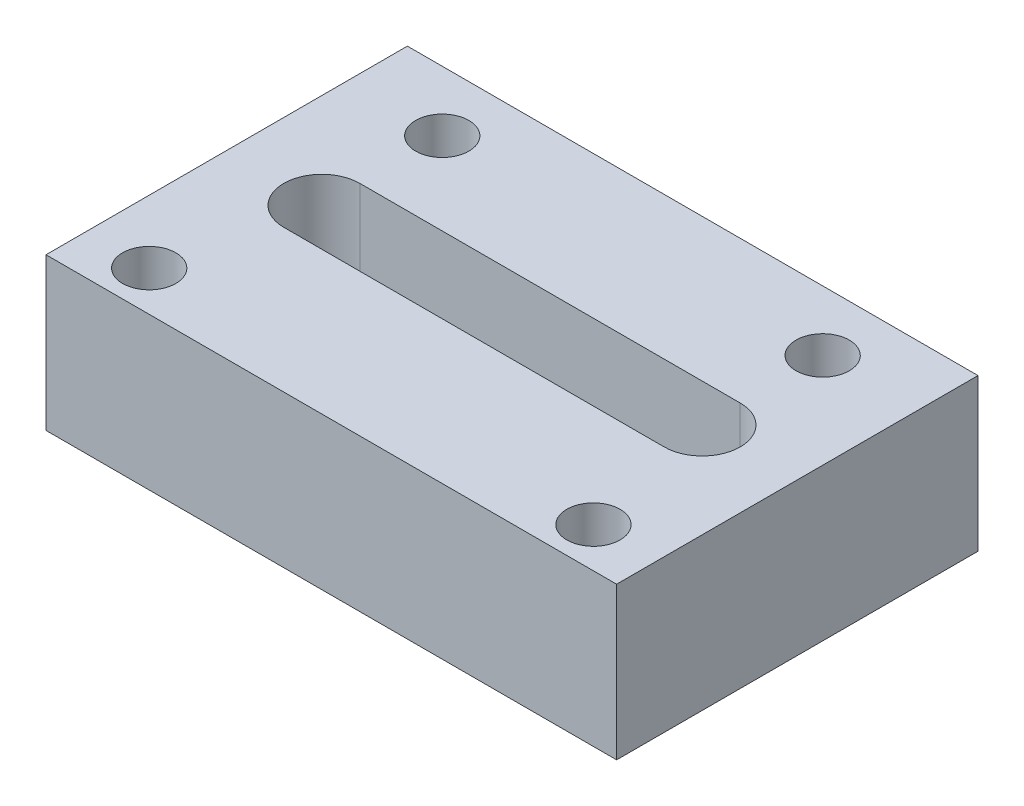
SolidWorks part; units mm, degrees
ref_plane "Front Plane" through (0, 0, 0) normal (0, 0, 1) x (1, 0, 0)
ref_plane "Top Plane" through (0, 0, 0) normal (0, 1, 0) x (1, 0, 0)
ref_plane "Right Plane" through (0, 0, 0) normal (1, 0, 0) x (0, 0, -1)
sketch "Sketch1" plane through (0, 0, 0) normal (0, 1, 0) x (1, 0, 0)
  line L0 (-50, 0) -> (50, 0) construction
  line L1 (-75, 47.5) -> (75, 47.5)
  line L2 (-75, 47.5) -> (-75, -47.5)
  line L3 (-75, -47.5) -> (75, -47.5)
  line L4 (75, 47.5) -> (75, -47.5)
  line L5 (-75, 47.5) -> (75, -47.5) construction
  line L6 (-75, -47.5) -> (75, 47.5) construction
  line L7 (-50, 10) -> (50, 10)
  line L8 (-50, -10) -> (50, -10)
  arc A0 (-50, 10) -> (-50, -10) centre (-50, 0) ccw
  arc A1 (50, -10) -> (50, 10) centre (50, 0) ccw
  circle A2 centre (-50, 31.6667) radius 7
  circle A3 centre (50, 31.6667) radius 7
  circle A4 centre (-58.3891, -36.9798) radius 7
  circle A5 centre (58.3891, -36.9798) radius 7
  point P0 (0, 0)
  point P8 (0, 0)
  point P21 (0, 0)
  dimension "D4" = 10
  dimension "D5" = 14
  dimension "D1" = 150
  dimension "D2" = 95
  dimension "D3" = 100
extrude "Boss-Extrude1" add sketch "Sketch1" along normal blind 30 and the other way blind 10
sketch "Sketch2" plane through (0, 0, -47.5) normal (0, 0, -1) x (-1, 0, 0)
